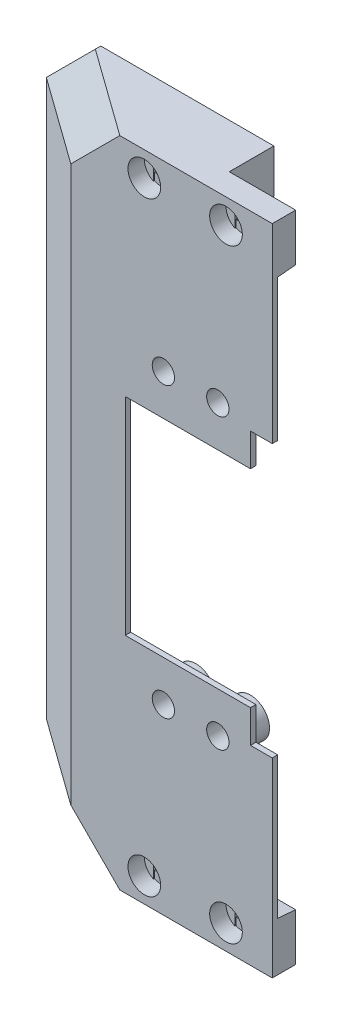
SolidWorks part; units mm, degrees
ref_plane "Front Plane" through (0, 0, 0) normal (0, 0, 1) x (1, 0, 0)
ref_plane "Top Plane" through (0, 0, 0) normal (0, 1, 0) x (1, 0, 0)
ref_plane "Right Plane" through (0, 0, 0) normal (1, 0, 0) x (0, 0, -1)
sketch "Sketch1" plane through (0, 0, 0) normal (0, 0, 1) x (1, 0, 0)
  line L0 (-38, 51) -> (-38, 58) construction
  line L1 (-45, 59.4) -> (-45, 51) construction
  line L2 (-45, -51) -> (-45, -59.4) construction
  line L3 (-38, -51) -> (-38, -58) construction
  line L4 (77, 60) -> (-77, 60) construction
  line L5 (-77, -60) -> (77, -60) construction
  line L6 (-86, -51) -> (-77, -60) construction
  line L7 (-86, 51) -> (-86, -51) construction
  line L8 (-77, 60) -> (-86, 51) construction
  line L9 (-38, 51) -> (-38, 58)
  line L10 (-45, 59.4) -> (-45, 51)
  line L11 (-45, -51) -> (-45, -59.4)
  line L12 (-38, -51) -> (-38, -58)
  line L13 (77, 60) -> (-77, 60)
  line L14 (-77, -60) -> (77, -60)
  line L15 (-86, -51) -> (-77, -60)
  line L16 (-86, 51) -> (-86, -51)
  line L17 (-77, 60) -> (-86, 51)
  circle A2 centre (-75.5, -55.5) radius 2.05 construction
  circle A3 centre (-75.5, 55.5) radius 2.05 construction
  circle A4 centre (-82, -30) radius 2.05 construction
  circle A5 centre (-75.5, -13.5) radius 2.05 construction
  circle A6 centre (-75.5, 13.5) radius 2.05 construction
  circle A7 centre (-82, 30) radius 2.05 construction
  circle A8 centre (-41.5, 55.5) radius 1.35
  circle A9 centre (-41.5, -55.5) radius 1.35
  circle A10 centre (-75.5, -55.5) radius 2.05
  circle A11 centre (-75.5, 55.5) radius 2.05
  circle A12 centre (-82, -30) radius 2.05
  circle A13 centre (-75.5, -13.5) radius 2.05
  circle A14 centre (-75.5, 13.5) radius 2.05
  circle A15 centre (-82, 30) radius 2.05
  circle A16 centre (-41.5, -55.5) radius 1.35 construction
  circle A17 centre (-41.5, 55.5) radius 1.35 construction
sketch "Sketch2" plane through (0, 0, 0) normal (0, 0, 1) x (1, 0, 0)
  line L0 (-86, -51) -> (-77, -60) construction
  line L1 (-86, 51) -> (-86, -51) construction
  line L2 (-77, 60) -> (-86, 51) construction
  line L3 (-86, -51) -> (-77, -60)
  line L4 (-86, 51) -> (-86, -51)
  line L5 (-77, 60) -> (-86, 51)
  line L6 (-77, 60) -> (-33, 60)
  line L7 (77, 60) -> (-77, 60) construction
  line L8 (-33, 60) -> (-33, -60)
  line L9 (-77, -60) -> (77, -60) construction
  line L10 (-33, -60) -> (-77, -60)
  line L11 (-38, -51) -> (-38, -58) construction
  dimension "D1" = 5
extrude "Boss-Extrude1" add sketch "Sketch2" along normal blind 1
ref_plane "Plane1" through (0, 0, 12.5) normal (0, 0, 1) x (1, 0, 0)
sketch "Sketch3" plane through (0, 0, 12.5) normal (0, 0, 1) x (1, 0, 0)
  line L0 (-33, 60) -> (-61, 60)
  line L1 (77, 60) -> (-77, 60) construction
  line L2 (-61, 60) -> (-70, 51)
  line L3 (-70, 51) -> (-70, -51)
  line L4 (-70, -51) -> (-61, -60)
  line L5 (-77, -60) -> (77, -60) construction
  line L6 (-61, -60) -> (-33, -60)
  line L7 (-33, -60) -> (-33, 60)
  line L8 (-77, 60) -> (-86, 51) construction
  line L9 (-86, -51) -> (-77, -60) construction
  line L10 (-86, 51) -> (-86, -51) construction
  dimension "D1" = 16
sketch "Sketch4" plane through (0, 0, 1) normal (0, 0, 1) x (1, 0, 0)
  line L6 (-86, 51) -> (-86, -51)
  line L7 (-86, -51) -> (-77, -60)
  line L8 (-77, -60) -> (-33, -60)
  line L9 (-33, -60) -> (-33, 60)
  line L10 (-33, 60) -> (-77, 60)
  line L11 (-77, 60) -> (-86, 51)
  line L12 (-86, 51) -> (-86, -51)
  line L13 (-86, -51) -> (-77, -60)
  line L14 (-77, -60) -> (-33, -60)
  line L15 (-33, -60) -> (-33, 60)
  line L16 (-33, 60) -> (-77, 60)
  line L17 (-77, 60) -> (-86, 51)
  dimension "D1" = 0
loft "Loft1" add profiles "Sketch4", "Sketch3"
sketch "Sketch5" plane through (0, 0, 0) normal (0, 0, -1) x (-1, 0, 0)
  line L0 (33, 52) -> (77, 52)
  line L1 (33, -60) -> (33, 60) construction
  line L2 (77, 52) -> (78, 51)
  line L3 (78, 51) -> (78, -51)
  line L4 (78, -51) -> (77, -52)
  line L5 (77, -52) -> (33, -52)
  line L6 (33, -52) -> (33, 52)
  line L7 (86, 51) -> (86, -51) construction
  line L8 (77, 60) -> (86, 51) construction
  line L9 (86, -51) -> (77, -60) construction
  line L10 (33, 60) -> (77, 60) construction
  point P4 (78, 0)
  point P11 (86, 0)
  point P17 (33, 0)
  dimension "D1" = 8
  dimension "D2" = 8
ref_plane "Plane2" through (0, 0, 11.5) normal (0, 0, 1) x (1, 0, 0)
sketch "Sketch6" plane through (0, 0, 11.5) normal (0, 0, 1) x (1, 0, 0)
  line L0 (-33, 51) -> (-64.3431, 51)
  line L1 (-33, -60) -> (-33, 60) construction
  line L2 (-64.3431, 51) -> (-66, 49.3431)
  line L3 (-66, 49.3431) -> (-66, -49.3431)
  line L4 (-66, -49.3431) -> (-64.3431, -51)
  line L5 (-64.3431, -51) -> (-33, -51)
  line L6 (-33, -51) -> (-33, 51)
  line L7 (-61, 60) -> (-70, 51) construction
  line L8 (-70, -51) -> (-61, -60) construction
  line L9 (-33, 60) -> (-61, 60) construction
  line L10 (-61, -60) -> (-33, -60) construction
  line L11 (-70, 51) -> (-70, -51) construction
  dimension "9" = 9
  dimension "D2" = 9
  dimension "D3" = 4
  dimension "D4" = 4
loft "Cut-Loft1" cut profiles "Sketch6", "Sketch5"
sketch "Sketch7" plane through (0, 0, 11.5) normal (0, 0, -1) x (-1, 0, 0)
  line L0 (33, -51) -> (33, 51) construction
  line L1 (33, 25) -> (37, 25)
  line L2 (33, 25) -> (33, -25)
  line L3 (33, -25) -> (37, -25)
  line L4 (37, 25) -> (37, -25)
  point P6 (37, 0)
  dimension "D1" = 4
  dimension "D2" = 50
extrude "Cut-Extrude1" cut sketch "Sketch7" against normal through all
sketch "Sketch8" plane through (0, -60, 0) normal (0, -1, 0) x (1, 0, 0)
  line L1 (-33, 0) -> (-45.2, 0)
  line L2 (-33, 0) -> (-33, 5.2)
  line L3 (-33, 5.2) -> (-45.2, 5.2)
  line L4 (-45.2, 0) -> (-45.2, 5.2)
  dimension "D1" = 5.2
  dimension "D2" = 12.2
extrude "Cut-Extrude2" cut sketch "Sketch8" against normal through all
sketch "Sketch9" plane through (0, 0, 12.5) normal (0, 0, 1) x (1, 0, 0)
  circle A0 centre (-41.5, -55.5) radius 1.35 construction
  circle A1 centre (-41.5, 55.5) radius 1.35 construction
  circle A2 centre (-41.5, -55.5) radius 1.35 construction
  circle A3 centre (-41.5, 55.5) radius 1.35 construction
  circle A4 centre (-41.5, 55.5) radius 1.35
  circle A5 centre (-41.5, -55.5) radius 1.35
  dimension "D1" = 2.7
extrude "Cut-Extrude3" cut sketch "Sketch9" against normal through all
sketch "Sketch10" plane through (0, 0, 12.5) normal (0, 0, 1) x (1, 0, 0)
  circle A0 centre (-41.5, 55.5) radius 3
  circle A1 centre (-41.5, -55.5) radius 3
  dimension "D1" = 6
extrude "Cut-Extrude4" cut sketch "Sketch10" against normal blind 3
sketch "Sketch14" plane through (0, 0, 9.5) normal (0, 0, 1) x (1, 0, 0)
  line L2 (-42.85, -58.1791) -> (-42.85, -52.8209)
  line L4 (-40.15, -58.1791) -> (-40.15, -52.8209)
  line L5 (-42.85, -58.1791) -> (-40.15, -52.8209) construction
  line L6 (-42.85, -52.8209) -> (-40.15, -58.1791) construction
  circle A0 centre (-41.5, -55.5) radius 3 construction
  circle A1 centre (-41.5, -55.5) radius 1.35 construction
  arc A2 (-40.15, -52.8209) -> (-42.85, -52.8209) centre (-41.5, -55.5) ccw
  arc A3 (-42.85, -58.1791) -> (-40.15, -58.1791) centre (-41.5, -55.5) ccw
  point P0 (-41.5, -55.5)
extrude "Cut-Extrude8" cut sketch "Sketch14" against normal blind 0.2
sketch "Sketch15" plane through (0, 0, 9.3) normal (0, 0, 1) x (1, 0, 0)
  line L0 (-40.15, -55.5) -> (-40.15, -52.8209) construction
  line L1 (-42.85, -56.85) -> (-40.15, -56.85)
  line L2 (-42.85, -56.85) -> (-42.85, -54.15)
  line L3 (-42.85, -54.15) -> (-40.15, -54.15)
  line L4 (-40.15, -56.85) -> (-40.15, -54.15)
  line L5 (-42.85, -56.85) -> (-40.15, -54.15) construction
  line L6 (-42.85, -54.15) -> (-40.15, -56.85) construction
  point P0 (-41.5, -55.5)
extrude "Cut-Extrude9" cut sketch "Sketch15" against normal blind 0.2
mirror "Mirror1" about plane through (0, 0, 0) normal (0, 1, 0) of "Cut-Extrude8", "Cut-Extrude9"
sketch "Sketch16" plane through (0, 0, 11.5) normal (0, 0, -1) x (-1, 0, 0)
  line L0 (0, 0) -> (86, 0) construction
  line L1 (86, 51) -> (86, -51) construction
  line L3 (43, -26.5) -> (53, -26.5) construction
  line L4 (43, -26.5) -> (43, 26.5) construction
  line L5 (43, 26.5) -> (53, 26.5) construction
  line L6 (53, -26.5) -> (53, 26.5) construction
  line L7 (43, -26.5) -> (53, 26.5) construction
  line L8 (43, 26.5) -> (53, -26.5) construction
  line L9 (66, 49.3431) -> (66, -49.3431) construction
  circle A0 centre (43, 26.5) radius 2.05
  circle A1 centre (53, 26.5) radius 2.05
  circle A2 centre (53, -26.5) radius 2.05
  circle A3 centre (43, -26.5) radius 2.05
  point P5 (48, 0)
  dimension "D1" = 4.1
  dimension "D2" = 53
  dimension "D3" = 10
  dimension "D4" = 13
extrude "Cut-Extrude10" cut sketch "Sketch16" against normal through all
sketch "Sketch17" plane through (0, 0, 11.5) normal (0, 0, -1) x (-1, 0, 0)
  circle A0 centre (43, -26.5) radius 2.05 construction
  circle A1 centre (53, -26.5) radius 2.05 construction
  circle A2 centre (53, 26.5) radius 2.05 construction
  circle A3 centre (43, 26.5) radius 2.05 construction
  circle A4 centre (43, -26.5) radius 2.05
  circle A5 centre (53, -26.5) radius 2.05
  circle A6 centre (53, 26.5) radius 2.05
  circle A7 centre (43, 26.5) radius 2.05
  circle A8 centre (43, 26.5) radius 3.5
  circle A9 centre (53, 26.5) radius 3.5
  circle A10 centre (53, -26.5) radius 3.5
  circle A11 centre (43, -26.5) radius 3.5
  dimension "D1" = 7
extrude "Boss-Extrude2" add sketch "Sketch17" along normal blind 5
fillet "Fillet1" radius 1 4 edges at (-49.5, 26.5, 11.5) (-39.5, 26.5, 11.5) (-49.5, -26.5, 11.5) (-39.5, -26.5, 11.5)
sketch "Sketch18" plane through (0, 0, 11.5) normal (0, 0, -1) x (-1, 0, 0)
  line L0 (37, -25) -> (37, 25) construction
  line L1 (37, 11) -> (42, 11)
  line L2 (37, 11) -> (37, -11)
  line L3 (37, -11) -> (42, -11)
  line L4 (42, 11) -> (42, -11)
  point P6 (37, 0)
  dimension "D1" = 22
  dimension "D2" = 5
extrude "Cut-Extrude11" cut sketch "Sketch18" against normal through all
sketch "Sketch19" plane through (0, 60, 0) normal (0, 1, 0) x (1, 0, 0)
  line L0 (-33, -12.5) -> (-33, -5.2) construction
  line L1 (-45.2, -5.2) -> (-33, -5.2)
  line L2 (-45.2, -5.2) -> (-45.2, -8.2)
  line L3 (-45.2, -8.2) -> (-33, -8.2)
  line L4 (-33, -5.2) -> (-33, -8.2)
  dimension "D1" = 3
extrude "Cut-Extrude12" cut sketch "Sketch19" against normal up to surface (8.4522 mm away)
sketch "Sketch20" plane through (0, -60, 0) normal (0, -1, 0) x (1, 0, 0)
  line L0 (-33, 12.5) -> (-33, 5.2) construction
  line L1 (-45.2, 5.2) -> (-33, 5.2)
  line L2 (-45.2, 5.2) -> (-45.2, 8.2)
  line L3 (-45.2, 8.2) -> (-33, 8.2)
  line L4 (-33, 5.2) -> (-33, 8.2)
  dimension "D1" = 3
extrude "Cut-Extrude13" cut sketch "Sketch20" against normal up to surface (8.4522 mm away)
sketch "Sketch23" plane through (0, 0, 12.5) normal (0, 0, 1) x (1, 0, 0)
  circle A0 centre (-56.5, -55.5) radius 1.35
  point P3 (-41.5, -55.5)
  dimension "D1" = 2.7
  dimension "D2" = 15
extrude "Cut-Extrude14" cut sketch "Sketch23" against normal through all both and the other way through all
sketch "Sketch24" plane through (0, 0, 12.5) normal (0, 0, 1) x (1, 0, 0)
  circle A0 centre (-56.5, -55.5) radius 3
  circle A1 centre (-41.5, -55.5) radius 3 construction
extrude "Cut-Extrude15" cut sketch "Sketch24" against normal blind 3
sketch "Sketch25" plane through (0, 0, 9.5) normal (0, 0, 1) x (1, 0, 0)
  line L2 (-57.85, -58.1791) -> (-57.85, -52.8209)
  line L4 (-55.15, -58.1791) -> (-55.15, -52.8209)
  line L5 (-57.85, -58.1791) -> (-55.15, -52.8209) construction
  line L6 (-57.85, -52.8209) -> (-55.15, -58.1791) construction
  circle A0 centre (-56.5, -55.5) radius 3 construction
  circle A1 centre (-56.5, -55.5) radius 3 construction
  arc A2 (-55.15, -52.8209) -> (-57.85, -52.8209) centre (-56.5, -55.5) ccw
  circle A3 centre (-56.5, -55.5) radius 1.35 construction
  arc A4 (-57.85, -58.1791) -> (-55.15, -58.1791) centre (-56.5, -55.5) ccw
  point P0 (-56.5, -55.5)
extrude "Cut-Extrude16" cut sketch "Sketch25" against normal blind 0.2
sketch "Sketch26" plane through (0, 0, 9.3) normal (0, 0, 1) x (1, 0, 0)
  line L0 (-55.15, -55.5) -> (-55.15, -52.8209) construction
  line L1 (-57.85, -56.85) -> (-55.15, -56.85)
  line L2 (-57.85, -56.85) -> (-57.85, -54.15)
  line L3 (-57.85, -54.15) -> (-55.15, -54.15)
  line L4 (-55.15, -56.85) -> (-55.15, -54.15)
  line L5 (-57.85, -56.85) -> (-55.15, -54.15) construction
  line L6 (-57.85, -54.15) -> (-55.15, -56.85) construction
  arc A0 (-55.15, -55.5) -> (-57.85, -55.5) centre (-56.5, -55.5) ccw construction
  point P0 (-56.5, -55.5)
extrude "Cut-Extrude17" cut sketch "Sketch26" against normal blind 0.2
mirror "Mirror2" about plane through (0, 0, 0) normal (0, 1, 0) of "Cut-Extrude14", "Cut-Extrude15", "Cut-Extrude16", "Cut-Extrude17"
sketch "Sketch27" plane through (0, 0, 11.5) normal (0, 0, -1) x (-1, 0, 0)
  line L0 (37, 11) -> (37, 25) construction
  line L1 (37, 19) -> (60, 19)
  line L2 (37, 19) -> (37, -19)
  line L3 (37, -19) -> (60, -19)
  line L4 (60, 19) -> (60, -19)
  line L5 (33, 25) -> (33, 51) construction
  point P6 (60, 0)
  dimension "D1" = 27
  dimension "D2" = 38
extrude "Cut-Extrude18" cut sketch "Sketch27" against normal through all
